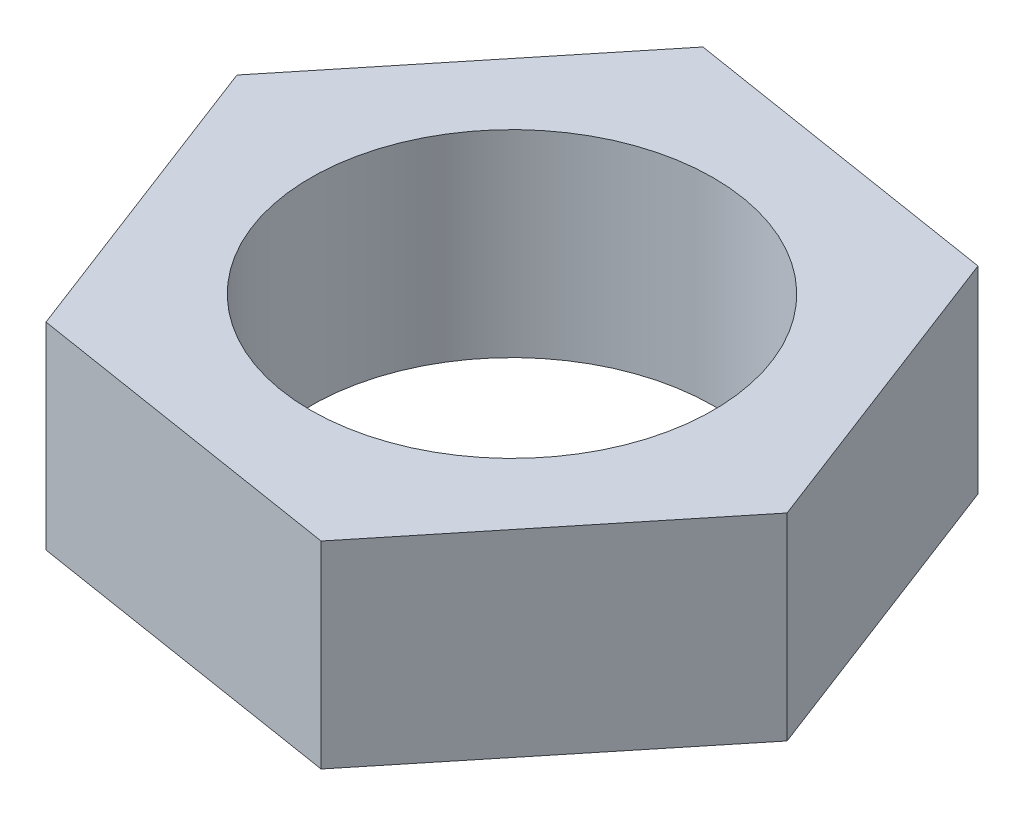
SolidWorks part; units mm, degrees
ref_plane "Front Plane" through (0, 0, 0) normal (0, 0, 1) x (1, 0, 0)
ref_plane "Top Plane" through (0, 0, 0) normal (0, 1, 0) x (1, 0, 0)
ref_plane "Right Plane" through (0, 0, 0) normal (1, 0, 0) x (0, 0, -1)
sketch "Sketch1" plane through (0, 0, 0) normal (0, 1, 0) x (1, 0, 0)
  line L1 (29.9995, -78.347) -> (82.8503, -13.1931)
  line L2 (82.8503, -13.1931) -> (52.8507, 65.1539)
  line L3 (52.8507, 65.1539) -> (-29.9995, 78.347)
  line L4 (-29.9995, 78.347) -> (-82.8503, 13.1931)
  line L5 (-82.8503, 13.1931) -> (-52.8507, -65.1539)
  line L6 (-52.8507, -65.1539) -> (29.9995, -78.347)
  circle A0 centre (0, 0) radius 72.6545 construction
extrude "Boss-Extrude1" add sketch "Sketch1" along normal blind 50
sketch "Sketch2" plane through (0, 50, 0) normal (0, 1, 0) x (1, 0, 0)
  circle A0 centre (0, 0) radius 50.9894
extrude "Cut-Extrude1" cut sketch "Sketch2" against normal through all
